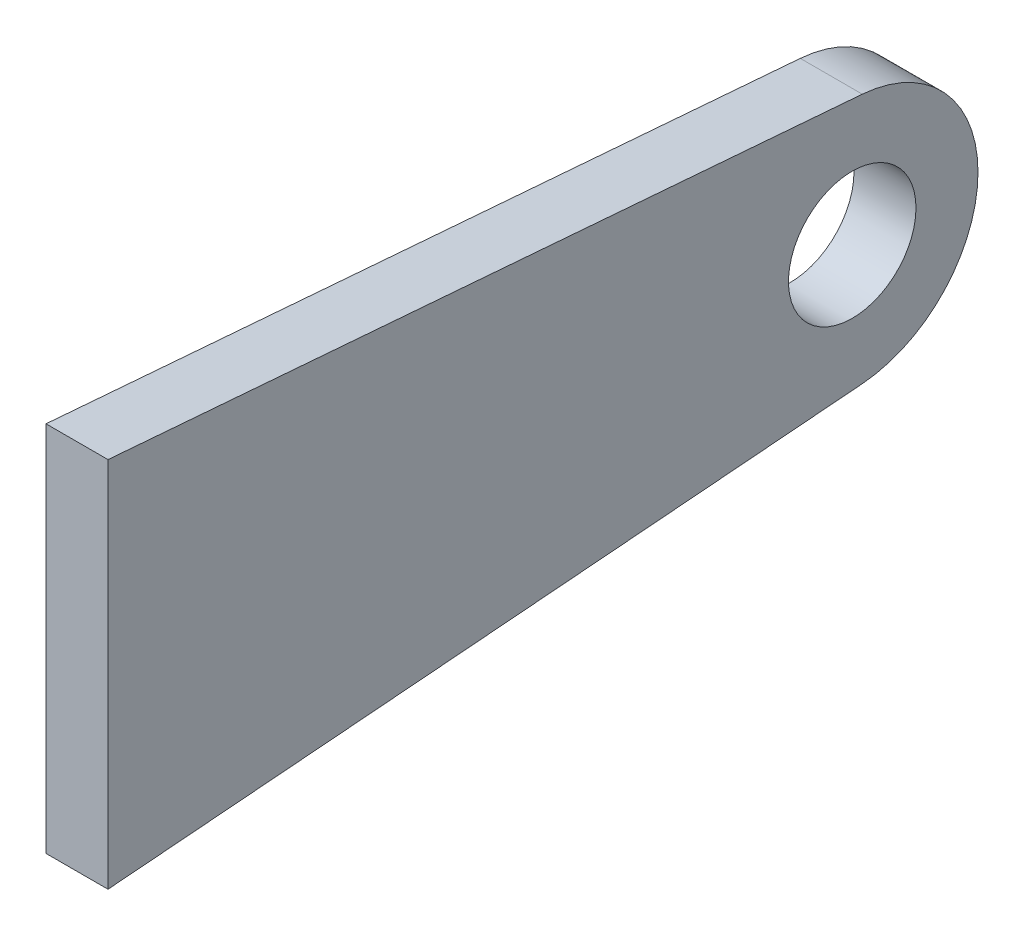
SolidWorks part; units mm, degrees
material "AISI 4130 Steel, annealed at 865C"
ref_plane "X-Y Datum" through (0, 0, 0) normal (0, 0, 1) x (1, 0, 0)
ref_plane "X-Z Datum" through (0, 0, 0) normal (0, 1, 0) x (1, 0, 0)
ref_plane "Y-Z Datum" through (0, 0, 0) normal (1, 0, 0) x (0, 0, -1)
sketch "Sketch1" plane through (0, 0, 0) normal (1, 0, 0) x (0, 0, -1)
  line L0 (0, 0) -> (-38.1, 0) construction
  line L1 (-38.1, 9.525) -> (-38.1, -9.525)
  line L2 (0.5164, 6.4182) -> (-38.1, 9.525)
  line L3 (0.5164, -6.4182) -> (-38.1, -9.525)
  circle A0 centre (0, 0) radius 3.2639
  arc A1 (0.5164, -6.4182) -> (0.5164, 6.4182) centre (0, 0) ccw
  point P3 (0, 0)
  point P7 (-38.1, 0)
  dimension "D1" = 6.5278
  dimension "D2" = 3.175
  dimension "D4" = 19.05
extrude "Boss-Extrude1" add sketch "Sketch1" along normal mid plane 3.175
